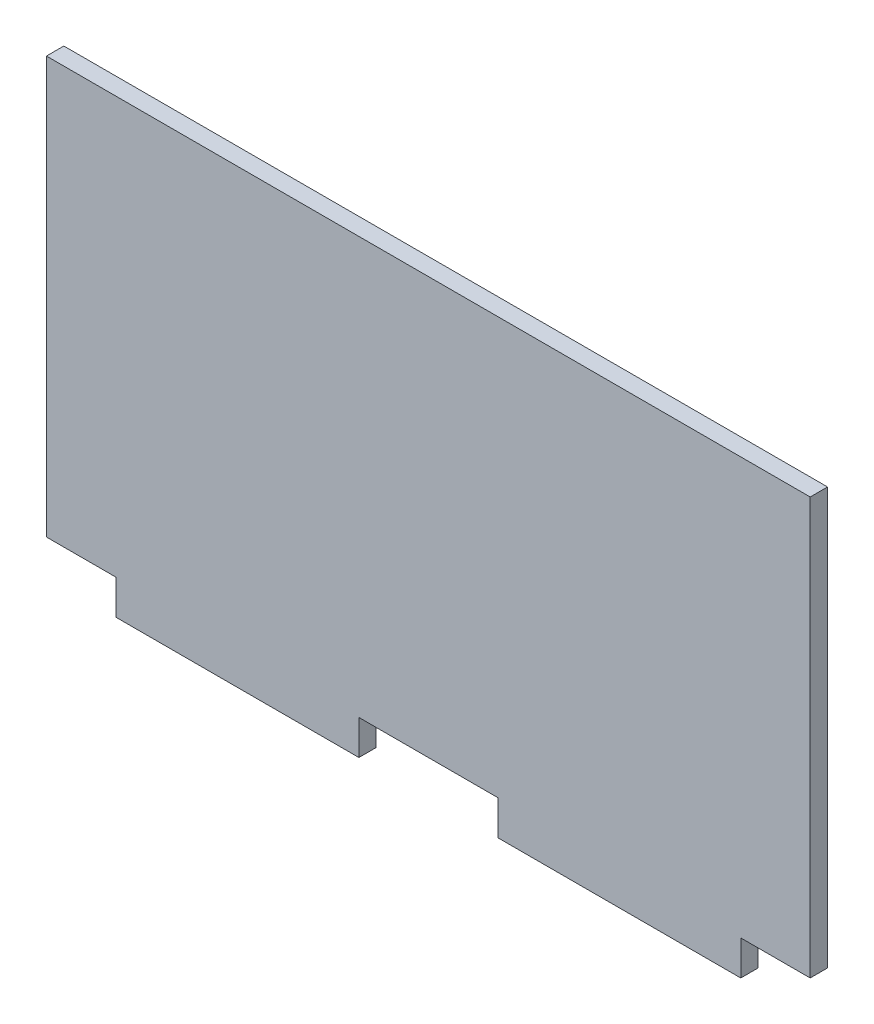
SolidWorks part; units mm, degrees
material "Balsa"
ref_plane "Plan de face" through (0, 0, 0) normal (0, 0, 1) x (1, 0, 0)
ref_plane "Plan de dessus" through (0, 0, 0) normal (0, 1, 0) x (1, 0, 0)
ref_plane "Plan de droite" through (0, 0, 0) normal (1, 0, 0) x (0, 0, -1)
sketch "Esquisse1" plane through (0, 0, 0) normal (0, 0, 1) x (1, 0, 0)
  line L0 (-75.624, 0) -> (-55.624, 0)
  line L1 (-55.624, 0) -> (-55.624, -10)
  line L2 (-55.624, -10) -> (14.376, -10)
  line L3 (14.376, -10) -> (14.376, 0)
  line L4 (14.376, 0) -> (54.376, 0)
  line L5 (54.376, 0) -> (54.376, -10)
  line L6 (54.376, -10) -> (124.376, -10)
  line L7 (124.376, -10) -> (124.376, 0)
  line L8 (124.376, 0) -> (144.376, 0)
  line L9 (144.376, 0) -> (144.376, 120)
  line L10 (144.376, 120) -> (-75.624, 120)
  line L11 (-75.624, 120) -> (-75.624, 0)
  dimension "D1" = 220
  dimension "D2" = 20
  dimension "D3" = 70
  dimension "D4" = 40
  dimension "D5" = 70
  dimension "D6" = 20
  dimension "D7" = 120
  dimension "D8" = 10
  dimension "D9" = 10
  dimension "D10" = 120
extrude "Boss.-Extru.1" add sketch "Esquisse1" along normal blind 5 contours L11 L0 L1 L2 L3 L4 L5 L6 L7 L8 L9 L10
